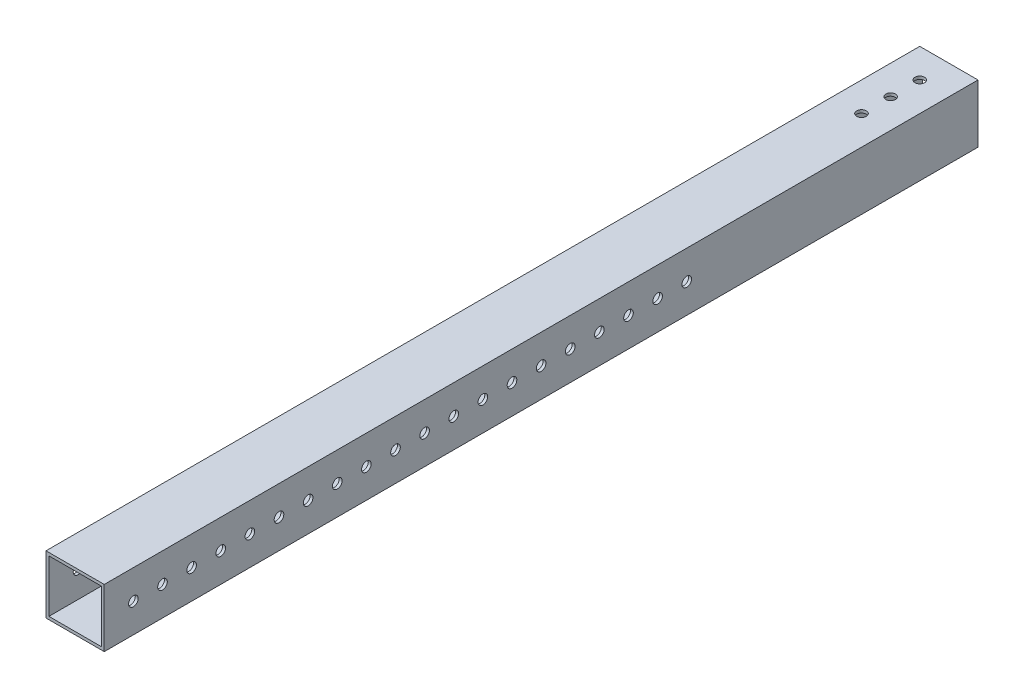
SolidWorks part; units mm, degrees
ref_plane "前视基准面" through (0, 0, 0) normal (0, 0, 1) x (1, 0, 0)
ref_plane "上视基准面" through (0, 0, 0) normal (0, 1, 0) x (1, 0, 0)
ref_plane "右视基准面" through (0, 0, 0) normal (1, 0, 0) x (0, 0, -1)
other "Configuration Table"
sketch "草图1" plane through (0, 0, 0) normal (0, 0, 1) x (1, 0, 0)
  line L1 (-10, 10) -> (10, 10)
  line L2 (-10, 10) -> (-10, -10)
  line L3 (-10, -10) -> (10, -10)
  line L4 (10, 10) -> (10, -10)
  line L5 (-10, 10) -> (10, -10) construction
  line L6 (-10, -10) -> (10, 10) construction
  line L7 (-9, 9) -> (9, 9)
  line L8 (-9, 9) -> (-9, -9)
  line L9 (-9, -9) -> (9, -9)
  line L10 (9, 9) -> (9, -9)
  line L11 (-9, 9) -> (9, -9) construction
  line L12 (-9, -9) -> (9, 9) construction
  point P0 (0, 0)
  point P6 (0, 0)
  dimension "D1" = 20
  dimension "D2" = 20
  dimension "D3" = 18
extrude "凸台-拉伸1" add sketch "草图1" along normal blind 300
sketch "草图2" plane through (0, 10, 0) normal (0, 1, 0) x (1, 0, 0)
  line L0 (0, 0) -> (0, -10) construction
  line L1 (0, -10) -> (0, -20) construction
  line L2 (0, -20) -> (0, -30) construction
  circle A0 centre (0, -10) radius 1.65
  circle A1 centre (0, -20) radius 1.65
  circle A2 centre (0, -30) radius 1.65
  dimension "D4" = 3.3
  dimension "D5" = 3.3
  dimension "D6" = 3.3
  dimension "D1" = 10
  dimension "D2" = 10
  dimension "D3" = 10
extrude "切除-拉伸1" cut sketch "草图2" against normal through all
sketch "草图4" plane through (10, 0, 0) normal (1, 0, 0) x (0, 0, -1)
  line L0 (-300, -10) -> (-300, 10) construction
  circle A0 centre (-290, 0) radius 1.65
  circle A1 centre (-280, 0) radius 1.65
  circle A2 centre (-270, 0) radius 1.65
  circle A3 centre (-260, 0) radius 1.65
  circle A4 centre (-250, 0) radius 1.65
  circle A5 centre (-240, 0) radius 1.65
  circle A6 centre (-230, 0) radius 1.65
  circle A7 centre (-220, 0) radius 1.65
  circle A8 centre (-210, 0) radius 1.65
  circle A9 centre (-200, 0) radius 1.65
  circle A10 centre (-190, 0) radius 1.65
  circle A11 centre (-180, 0) radius 1.65
  circle A12 centre (-170, 0) radius 1.65
  circle A13 centre (-160, 0) radius 1.65
  circle A14 centre (-150, 0) radius 1.65
  circle A15 centre (-140, 0) radius 1.65
  circle A16 centre (-130, 0) radius 1.65
  circle A17 centre (-120, 0) radius 1.65
  circle A18 centre (-110, 0) radius 1.65
  circle A19 centre (-100, 0) radius 1.65
  dimension "D2" = 3.3
  dimension "D1" = 10
  dimension "D3" = 20
extrude "切除-拉伸3" cut sketch "草图4" against normal blind 180
